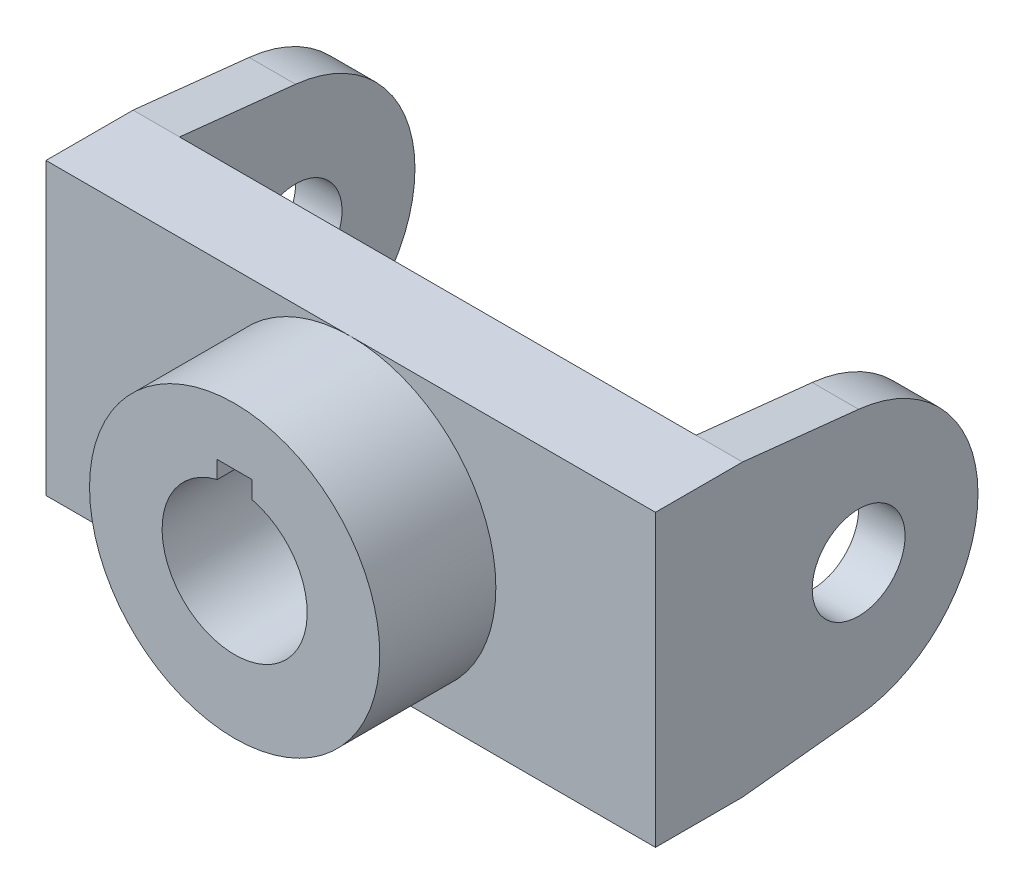
SolidWorks part; units mm, degrees
ref_plane "Front Plane" through (0, 0, 0) normal (0, 0, 1) x (1, 0, 0)
ref_plane "Top Plane" through (0, 0, 0) normal (0, 1, 0) x (1, 0, 0)
ref_plane "Right Plane" through (0, 0, 0) normal (1, 0, 0) x (0, 0, -1)
sketch "Sketch1" plane through (0, 0, 0) normal (0, 0, 1) x (1, 0, 0)
  line L1 (-52.5, 25) -> (52.5, 25)
  line L2 (-52.5, 25) -> (-52.5, -25)
  line L3 (-52.5, -25) -> (52.5, -25)
  line L4 (52.5, 25) -> (52.5, -25)
  line L5 (-52.5, 25) -> (52.5, -25) construction
  line L6 (-52.5, -25) -> (52.5, 25) construction
  point P0 (0, 0)
  dimension "D1" = 105
  dimension "D2" = 50
extrude "Boss-Extrude1" add sketch "Sketch1" along normal blind 15
sketch "Sketch4" plane through (-52.5, 0, 0) normal (-1, 0, 0) x (0, 0, 1)
  line L0 (0, 25) -> (-20, 22.8708)
  line L1 (0, -25) -> (-20, -22.8708)
  arc A0 (-20, 22.8708) -> (-20, -22.8708) centre (-17.5651, 0) ccw
  circle A2 centre (-20, 0) radius 8
  dimension "D3" = 23
  dimension "D4" = 16
  dimension "D1" = 35
  dimension "D2" = 35
extrude "Boss-Extrude2" add sketch "Sketch4" against normal blind 8
mirror "Mirror1" about plane through (0, 0, 0) normal (1, 0, 0) of "Boss-Extrude2"
sketch "Sketch5" plane through (0, 0, 15) normal (0, 0, 1) x (1, 0, 0)
  line L0 (0, 0) -> (0, 34.0155) construction
  line L1 (3, 12.1347) -> (3, 15.1347)
  line L2 (3, 15.1347) -> (-3, 15.1347)
  line L3 (-3, 12.1347) -> (-3, 15.1347)
  circle A0 centre (0, 0) radius 25
  arc A1 (-3, 12.1347) -> (3, 12.1347) centre (0, 0) ccw
  point P10 (0, 15.1347)
  dimension "D1" = 50
  dimension "D2" = 25
  dimension "D3" = 6
  dimension "D4" = 3
extrude "Boss-Extrude3" add sketch "Sketch5" along normal blind 20
